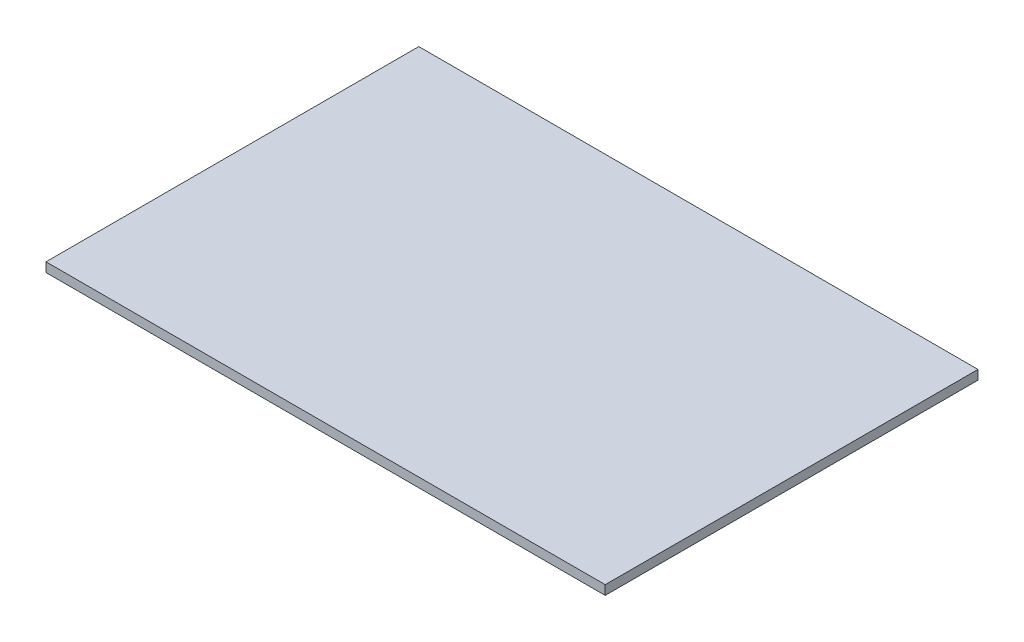
SolidWorks part; units mm, degrees
ref_plane "Plan de face" through (0, 0, 0) normal (0, 0, 1) x (1, 0, 0)
ref_plane "Plan de dessus" through (0, 0, 0) normal (0, 1, 0) x (1, 0, 0)
ref_plane "Plan de droite" through (0, 0, 0) normal (1, 0, 0) x (0, 0, -1)
sketch "Esquisse1" plane through (0, 0, 0) normal (0, 1, 0) x (1, 0, 0)
  line L0 (0, 0) -> (0, 1000) construction
  line L1 (-1500, 1000) -> (1500, 1000)
  line L2 (-1500, 1000) -> (-1500, -1000)
  line L3 (-1500, -1000) -> (1500, -1000)
  line L4 (1500, 1000) -> (1500, -1000)
  line L5 (0, 0) -> (1500, 0) construction
  dimension "D1" = 3000
  dimension "D2" = 2000
extrude "Extrusion1" add sketch "Esquisse1" along normal blind 50
